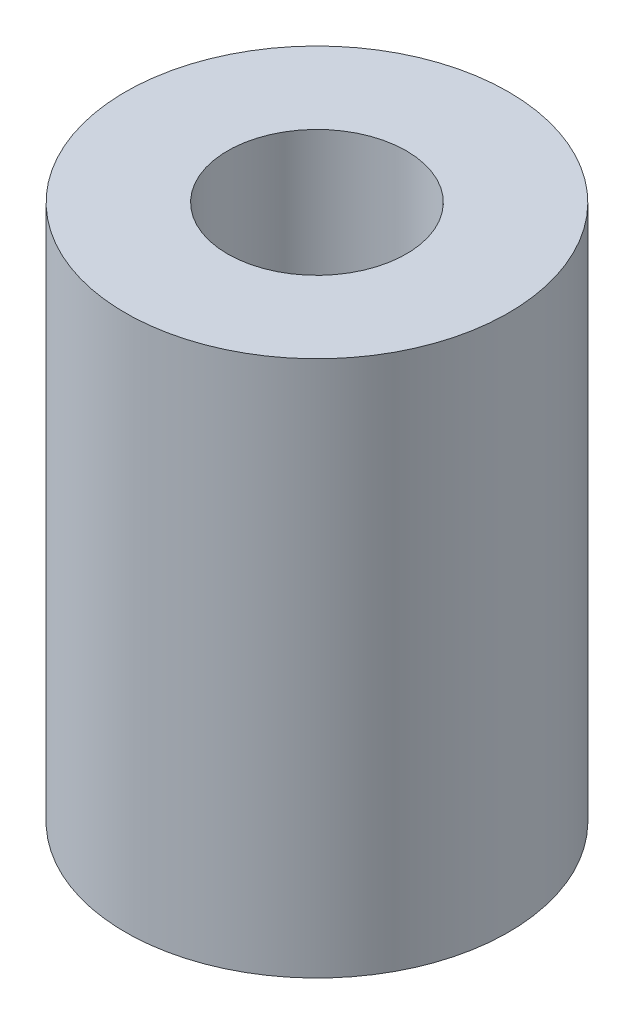
SolidWorks part; units mm, degrees
ref_plane "Front Plane" through (0, 0, 0) normal (0, 0, 1) x (1, 0, 0)
ref_plane "Top Plane" through (0, 0, 0) normal (0, 1, 0) x (1, 0, 0)
ref_plane "Right Plane" through (0, 0, 0) normal (1, 0, 0) x (0, 0, -1)
sketch "Sketch1" plane through (0, 0, 0) normal (0, 1, 0) x (1, 0, 0)
  circle A0 centre (0, 0) radius 3.75
  dimension "D1" = 7.5
extrude "Boss-Extrude1" add sketch "Sketch1" along normal blind 10.5
hole_wizard "Ø3.5 (3.5) Diameter Hole1" positions "Sketch2" profile "Sketch3" hole size "Ø3.5" standard "JIS" end condition through all
sketch "Sketch2" plane through (0, 10.5, 0) normal (0, 1, 0) x (1, 0, 0)
  point P0 (0, 0)
sketch "Sketch3" plane through (0, 10.5, 0) normal (1, 0, 0) x (0, 0, 1)
  line L0 (0, 0) -> (0, 10.5)
  line L1 (0, 10.5) -> (1.75, 10.5)
  line L2 (1.75, 10.5) -> (1.75, 0)
  line L5 (1.75, 0) -> (0, 0)
  line L11 (0, -6.35) -> (0, 107.95) construction
  dimension "Thru Hole Dia." = 3.5
  dimension "Thru Hole Depth" = 10.5
